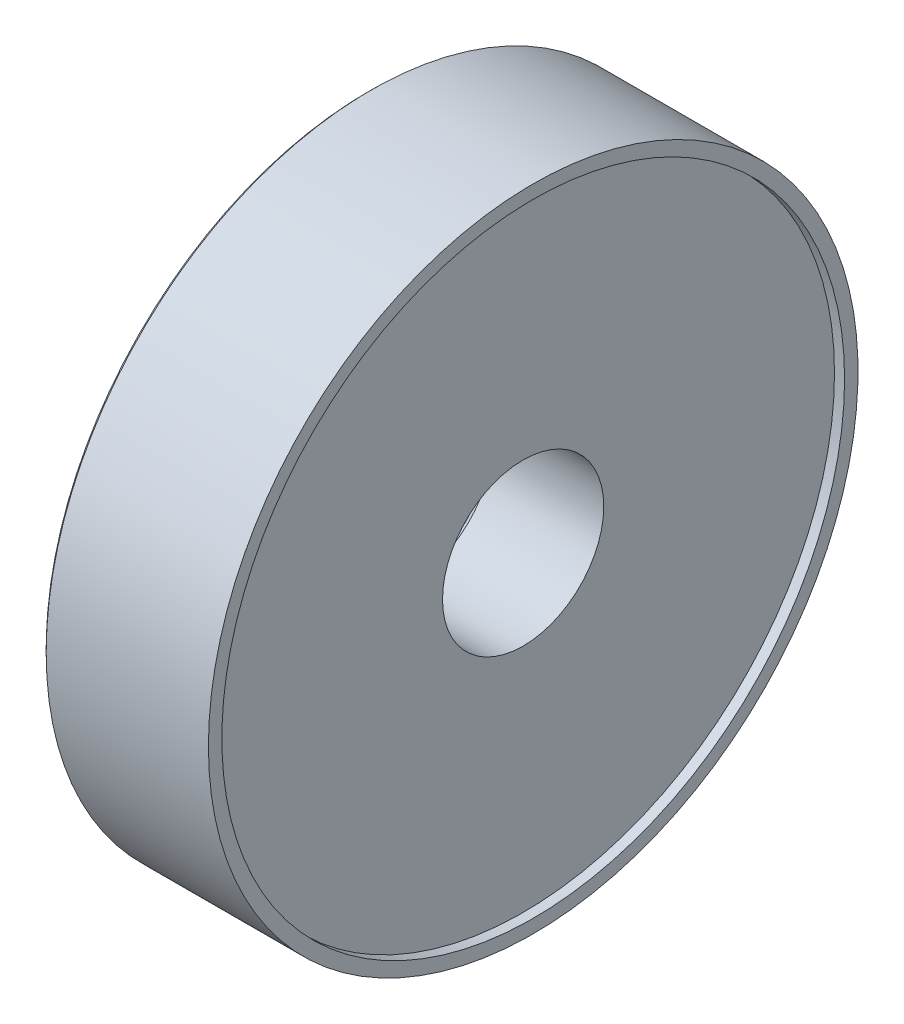
SolidWorks part; units mm, degrees
ref_plane "Front Plane" through (0, 0, 0) normal (0, 0, 1) x (1, 0, 0)
ref_plane "Top Plane" through (0, 0, 0) normal (0, 1, 0) x (1, 0, 0)
ref_plane "Right Plane" through (0, 0, 0) normal (1, 0, 0) x (0, 0, -1)
sketch "Sketch1" plane through (0, 0, 0) normal (1, 0, 0) x (0, 0, -1)
  circle A0 centre (0, 0) radius 48.35
  dimension "D1" = 96.7
extrude "Boss-Extrude1" add sketch "Sketch1" along normal mid plane 25.15
sketch "Sketch2" plane through (-12.575, 0, 0) normal (-1, 0, 0) x (0, 0, 1)
  line L0 (0, 0) -> (0, 43.35) construction
  circle A0 centre (0, 0) radius 43.35 construction
  circle A1 centre (0, 43.35) radius 1.25
  dimension "D1" = 86.7
  dimension "D2" = 2.5
extrude "Cut-Extrude1" cut sketch "Sketch2" against normal blind 3
chamfer "Chamfer1" distance 0.5 angle 45 1 edges at (-12.575, 43.35, 1.25)
pattern_circular "CirPattern1" count 6 over 360 about axis through (0, 0, 0) along (1, 0, 0) of "Cut-Extrude1", "Chamfer1"
sketch "Sketch3" plane through (-12.575, 0, 0) normal (-1, 0, 0) x (0, 0, 1)
  circle A0 centre (0, 0) radius 12
  dimension "D1" = 24
extrude "Cut-Extrude2" cut sketch "Sketch3" against normal up to surface (25.15 mm away) up to face at (12.575, 0, -48.35)
chamfer "Chamfer2" distance 1.25 angle 45 1 edges at (-12.575, 0, 12)
chamfer "Chamfer3" distance 0.5 angle 45 1 edges at (-12.575, 0, -48.35)
sketch "Sketch4" plane through (-12.575, 0, 0) normal (-1, 0, 0) x (0, 0, 1)
  circle A0 centre (0, 0) radius 28.25
  dimension "D1" = 56.5
extrude "Cut-Extrude3" cut sketch "Sketch4" against normal blind 5.35
sketch "Sketch5" plane through (-7.225, 0, 0) normal (-1, 0, 0) x (0, 0, 1)
  line L1 (-15.5, -15.5) -> (15.5, -15.5) construction
  line L2 (-15.5, -15.5) -> (-15.5, 15.5) construction
  line L3 (-15.5, 15.5) -> (15.5, 15.5) construction
  line L4 (15.5, -15.5) -> (15.5, 15.5) construction
  line L5 (-15.5, -15.5) -> (15.5, 15.5) construction
  line L6 (-15.5, 15.5) -> (15.5, -15.5) construction
  circle A0 centre (-15.5, 15.5) radius 3.5
  circle A1 centre (15.5, 15.5) radius 3.5
  circle A2 centre (15.5, -15.5) radius 3.5
  circle A3 centre (-15.5, -15.5) radius 3.5
  point P0 (0, 0)
  dimension "D2" = 7
  dimension "D1" = 31
extrude "Boss-Extrude2" add sketch "Sketch5" along normal blind 3.85
sketch "Sketch6" plane through (-11.075, 0, 0) normal (-1, 0, 0) x (0, 0, 1)
  circle A0 centre (-15.5, 15.5) radius 1.25
  circle A1 centre (15.5, 15.5) radius 1.25
  circle A2 centre (15.5, -15.5) radius 1.25
  circle A3 centre (-15.5, -15.5) radius 1.25
  dimension "D1" = 2.5
extrude "Cut-Extrude4" cut sketch "Sketch6" against normal blind 5.85
sketch "Sketch7" plane through (12.575, 0, 0) normal (1, 0, 0) x (0, 0, -1)
  circle A0 centre (0, 0) radius 46.35
  circle A1 centre (0, 0) radius 48.35 construction
  circle A4 centre (0, 0) radius 30.75
  circle A5 centre (0, 0) radius 30.75 construction
  dimension "D1" = 2
  dimension "D2" = 2.5
extrude "Cut-Extrude5" cut sketch "Sketch7" against normal blind 2
sketch "Sketch8" plane through (12.575, 0, 0) normal (1, 0, 0) x (0, 0, -1)
  circle A0 centre (0, 0) radius 46.35 construction
  circle A1 centre (0, 0) radius 48.35
  circle A2 centre (0, 0) radius 48.35
  circle A3 centre (0, 0) radius 46.35
  dimension "D1" = 0
extrude "Cut-Extrude6" cut sketch "Sketch8" against normal blind 0.5
chamfer "Chamfer4" distance 1.25 angle 45 1 edges at (-7.225, 0, 12)
